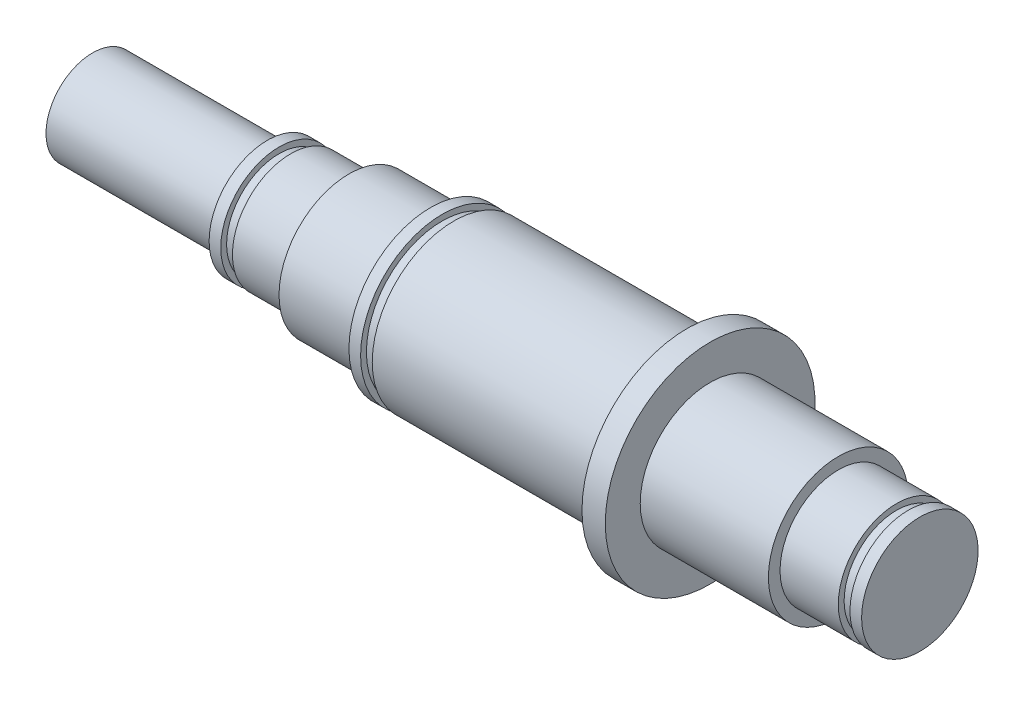
SolidWorks part; units mm, degrees
ref_plane "前视基准面" through (0, 0, 0) normal (0, 0, 1) x (1, 0, 0)
ref_plane "上视基准面" through (0, 0, 0) normal (0, 1, 0) x (1, 0, 0)
ref_plane "右视基准面" through (0, 0, 0) normal (1, 0, 0) x (0, 0, -1)
sketch "草图1" plane through (0, 0, 0) normal (0, 0, 1) x (1, 0, 0)
  line L0 (0, 0) -> (462.0683, 0) construction
  line L1 (0, 0) -> (0, 4)
  line L2 (0, 4) -> (15, 4)
  line L3 (15, 4) -> (15, 5)
  line L4 (15, 5) -> (16, 5)
  line L5 (16, 5) -> (16, 4.5)
  line L6 (16, 4.5) -> (17, 4.5)
  line L7 (17, 4.5) -> (17, 5)
  line L8 (17, 5) -> (22, 5)
  line L9 (22, 5) -> (22, 6)
  line L10 (22, 6) -> (29, 6)
  line L11 (29, 6) -> (29, 7)
  line L12 (29, 7) -> (30, 7)
  line L13 (30, 7) -> (30, 6.5)
  line L14 (30, 6.5) -> (31, 6.5)
  line L15 (31, 6.5) -> (31, 7)
  line L16 (31, 7) -> (51, 7)
  line L17 (51, 7) -> (51, 9)
  line L18 (51, 9) -> (53, 9)
  line L19 (53, 9) -> (53, 6)
  line L20 (53, 6) -> (64, 6)
  line L21 (64, 6) -> (64, 5)
  line L22 (64, 5) -> (69, 5)
  line L23 (69, 5) -> (69, 4.5)
  line L24 (69, 4.5) -> (70, 4.5)
  line L25 (70, 4.5) -> (70, 5)
  line L26 (70, 5) -> (71, 5)
  line L27 (71, 5) -> (71, 0)
  line L28 (0, 0) -> (71, 0)
  dimension "D1" = 4
  dimension "D2" = 5
  dimension "D3" = 15
  dimension "D4" = 4.5
  dimension "D5" = 5
  dimension "D6" = 1
  dimension "D7" = 5
  dimension "D8" = 1
  dimension "D9" = 7
  dimension "D10" = 6
  dimension "D11" = 7
  dimension "D12" = 7
  dimension "D13" = 1
  dimension "D14" = 6.5
  dimension "D15" = 1
  dimension "D16" = 20
  dimension "D17" = 9
  dimension "D18" = 2
  dimension "D19" = 11
  dimension "D20" = 6
  dimension "D21" = 5
  dimension "D22" = 5
  dimension "D23" = 4.5
  dimension "D24" = 1
  dimension "D25" = 1
  dimension "D26" = 5
revolve "旋转1" add sketch "草图1" angle 360 about L0
